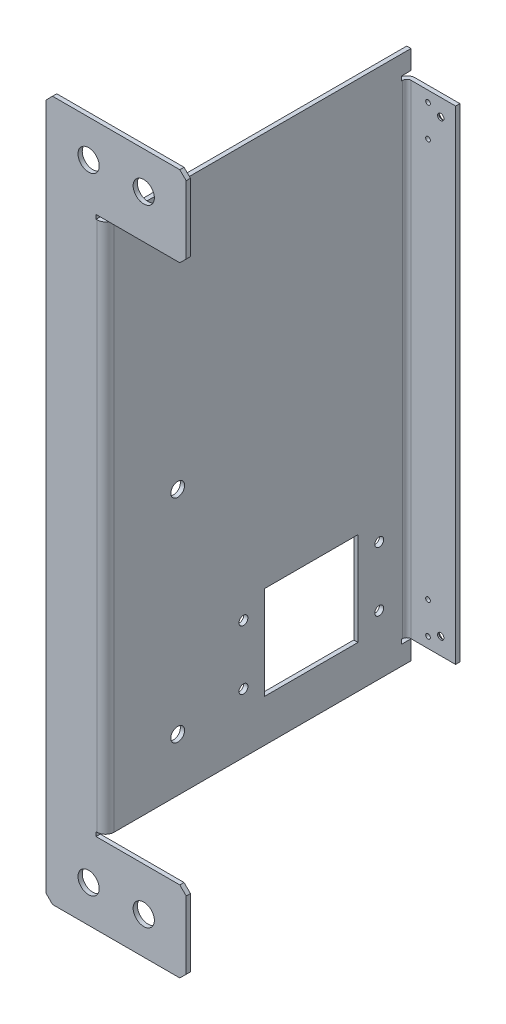
SolidWorks part; units mm, degrees
ref_plane "Спереди" through (0, 0, 0) normal (0, 0, 1) x (1, 0, 0)
ref_plane "Сверху" through (0, 0, 0) normal (0, 1, 0) x (1, 0, 0)
ref_plane "Справа" through (0, 0, 0) normal (1, 0, 0) x (0, 0, -1)
sketch "Эскиз1" plane through (0, 0, 0) normal (0, 0, 1) x (1, 0, 0)
  line L0 (-43.6006, 0) -> (53.6851, 0) construction
  line L1 (-15.3894, -165) -> (44.6106, -165)
  line L2 (-18.3894, -162) -> (-18.3894, 162)
  line L3 (-15.3894, 165) -> (44.6106, 165)
  line L4 (47.6106, -162) -> (47.6106, -130)
  line L5 (47.6106, 130) -> (47.6106, 162)
  line L6 (44.6106, -127) -> (9.6106, -127)
  line L7 (-37.9272, -147.5) -> (69.1915, -147.5) construction
  line L8 (44.6106, 127) -> (9.6106, 127)
  line L9 (9.6106, -127) -> (9.6106, 127)
  line L10 (-43.6006, 147.5) -> (58.9409, 147.5) construction
  line L11 (-18.3894, 162) -> (-15.3894, 165)
  line L12 (44.6106, 165) -> (47.6106, 162)
  line L13 (44.6106, 127) -> (47.6106, 130)
  line L14 (47.6106, -130) -> (44.6106, -127)
  line L15 (44.6106, -165) -> (47.6106, -162)
  line L16 (-18.3894, -162) -> (-15.3894, -165)
  circle A0 centre (1.6106, -147.5) radius 5
  circle A1 centre (27.6106, -147.5) radius 5
  circle A2 centre (27.6106, 147.5) radius 5
  circle A3 centre (1.6106, 147.5) radius 5
  point P0 (-18.3894, -165)
  point P1 (47.6106, 165)
  point P2 (-18.3894, 165)
  point P3 (47.6106, -165)
  point P6 (47.6106, -127)
  point P8 (47.6106, 127)
  dimension "D6" = 20
  dimension "D7" = 26
  dimension "D8" = 10
  dimension "D1" = 330
  dimension "D2" = 66
  dimension "D3" = 38
  dimension "D4" = 295
  dimension "D5" = 35
  dimension "D9" = 28
  dimension "D12" = 3
  dimension "D13" = 3
  dimension "D14" = 3
  dimension "D15" = 3
  dimension "D16" = 3
  dimension "D17" = 3
extrude "Вытянуть1" add sketch "Эскиз1" along normal blind 2
sketch "Эскиз2" plane through (0, 0, 2) normal (0, 0, 1) x (1, 0, 0)
  line L0 (-77.0675, 0) -> (63.9758, 0) construction
  line L1 (9.6106, -127) -> (9.6106, 127) construction
  line L2 (9.6106, -125) -> (7.6106, -125)
  line L3 (9.6106, -125) -> (9.6106, 125)
  line L4 (9.6106, 125) -> (7.6106, 125)
  line L5 (7.6106, -125) -> (7.6106, 125)
  dimension "D1" = 2
  dimension "D2" = 250
extrude "Вытянуть2" add sketch "Эскиз2" against normal blind 144
sketch "Эскиз3" plane through (9.6106, 0, 0) normal (1, 0, 0) x (0, 0, -1)
  line L0 (-20.1669, 0) -> (172.2564, 0) construction
  line L1 (142, -125) -> (142, 125) construction
  line L2 (140, -114) -> (142, -114)
  line L3 (140, -114) -> (140, 114)
  line L4 (140, 114) -> (142, 114)
  line L5 (142, -114) -> (142, 114)
  dimension "D1" = 2
  dimension "D2" = 228
extrude "Вытянуть3" add sketch "Эскиз3" along normal blind 23
sketch "Эскиз4" plane through (0, 0, 2) normal (0, 0, 1) x (1, 0, 0)
  line L0 (-8.6712, 0) -> (62.9395, 0) construction
  line L1 (9.6106, 127) -> (5.1106, 127)
  line L2 (9.6106, 127) -> (9.6106, 125)
  line L3 (9.6106, 125) -> (5.1106, 125)
  line L4 (5.1106, 127) -> (5.1106, 125)
  line L5 (9.6106, 127) -> (44.6106, 127) construction
  line L6 (9.6106, -125) -> (5.1106, -125)
  line L7 (9.6106, -127) -> (9.6106, -125)
  line L8 (9.6106, -127) -> (5.1106, -127)
  line L9 (5.1106, -127) -> (5.1106, -125)
  dimension "D1" = 4.5
  dimension "D2" = 2
extrude "Вырез-Вытянуть1" cut sketch "Эскиз4" against normal blind 2
sketch "Эскиз5" plane through (9.6106, 0, 0) normal (1, 0, 0) x (0, 0, -1)
  line L0 (-17.691, 0) -> (90.0382, 0) construction
  line L1 (142, -114) -> (137.5, -114)
  line L2 (142, -114) -> (142, -116)
  line L3 (142, -116) -> (137.5, -116)
  line L4 (137.5, -114) -> (137.5, -116)
  line L5 (142, 116) -> (137.5, 116)
  line L6 (142, 114) -> (142, 116)
  line L7 (142, 114) -> (137.5, 114)
  line L8 (137.5, 114) -> (137.5, 116)
  dimension "D1" = 2
  dimension "D2" = 4.5
extrude "Вырез-Вытянуть2" cut sketch "Эскиз5" against normal blind 2
fillet "Скругление3" radius 2
fillet "Скругление4" radius 4
sketch "Эскиз6" plane through (0, 0, -142) normal (0, 0, -1) x (-1, 0, 0)
  line L0 (0, 0) -> (-64.9274, 0) construction
  line L1 (-32.6106, -114) -> (-32.6106, 114) construction
  line L2 (-32.6106, -114) -> (-11.6106, -114) construction
  line L3 (-23.6106, 0) -> (-23.6106, 51.0302) construction
  line L6 (-32.6106, 114) -> (-11.6106, 114) construction
  line L7 (-19.6106, 121.5286) -> (-19.6106, -127) construction
  line L8 (-44.6106, -127) -> (-5.1106, -127) construction
  circle A0 centre (-19.6106, -94) radius 1.1
  circle A1 centre (-25.6106, -106) radius 1.5
  circle A2 centre (-25.6106, 106) radius 1.5
  circle A3 centre (-19.6106, -109) radius 1.1
  circle A5 centre (-19.6106, 109) radius 1.1
  circle A6 centre (-19.6106, 94) radius 1.1
  dimension "D2" = 2.2
  dimension "D3" = 7
  dimension "D4" = 8
  dimension "D5" = 3
  dimension "D6" = 2.2
  dimension "D11" = 15
  dimension "D12" = 5
  dimension "D10" = 13
extrude "Вырез-Вытянуть3" cut sketch "Эскиз6" against normal blind 2
cosmetic thread "Условное изображение резьбы1" parameters "D1"=2, "D2"=4
cosmetic thread "Условное изображение резьбы5" parameters "D1"=2, "D2"=3
cosmetic thread "Условное изображение резьбы6" parameters "D1"=2, "D2"=3
cosmetic thread "Условное изображение резьбы7" parameters "D1"=2, "D2"=3
cosmetic thread "Условное изображение резьбы8" parameters "D1"=2, "D2"=3
chamfer "Фаска1" distance 1.3 angle 45
sketch "Эскиз8" plane through (9.6106, 0, 0) normal (1, 0, 0) x (0, 0, -1)
  line L0 (32, 0) -> (118.9089, 0) construction
  line L2 (-2, -162) -> (-2, -130) construction
  line L3 (32, 99.2174) -> (32, -101.1338) construction
  line L4 (62.9471, -97) -> (63.0529, -97) construction
  line L5 (117, -105) -> (73, -105)
  line L6 (117, -105) -> (117, -61)
  line L7 (117, -61) -> (73, -61)
  line L8 (195.339, -69) -> (135.0529, -69) construction
  line L9 (73, -105) -> (73, -61)
  line L10 (142, -125) -> (2, -125) construction
  line L11 (-2, 162) -> (-2, -162) construction
  circle A0 centre (32, 0) radius 3.25
  circle A1 centre (32, -100) radius 3.25
  circle A2 centre (32, 100) radius 3.25
  circle A3 centre (63, -97) radius 2.1
  circle A4 centre (127, -97) radius 2.1
  circle A5 centre (127, -69) radius 2.1
  circle A6 centre (63, -69) radius 2.1
  dimension "D1" = 6.5
  dimension "D3" = 100
  dimension "D5" = 10
  dimension "D6" = 10
  dimension "D8" = 10
  dimension "D9" = 10
  dimension "D15" = 34
  dimension "D16" = 100
  dimension "D10" = 4.2
  dimension "D11" = 28
  dimension "D2" = 34
  dimension "D4" = 125
  dimension "D7" = 28
  dimension "D12" = 44
  dimension "D13" = 20
  dimension "D14" = 44
  dimension "D17" = 41
extrude "Вырез-Вытянуть4" cut sketch "Эскиз8" against normal blind 2
cosmetic thread "Условное изображение резьбы2" parameters "D1"=2, "D2"=3
cosmetic thread "Условное изображение резьбы3" parameters "D1"=2, "D2"=3
cosmetic thread "Условное изображение резьбы4" parameters "D1"=2, "D2"=4
cosmetic thread "Условное изображение резьбы9" parameters "D1"=1, "D2"=5
cosmetic thread "Условное изображение резьбы10" parameters "D1"=1, "D2"=5
cosmetic thread "Условное изображение резьбы11" parameters "D1"=1, "D2"=5
cosmetic thread "Условное изображение резьбы12" parameters "D1"=1, "D2"=5
